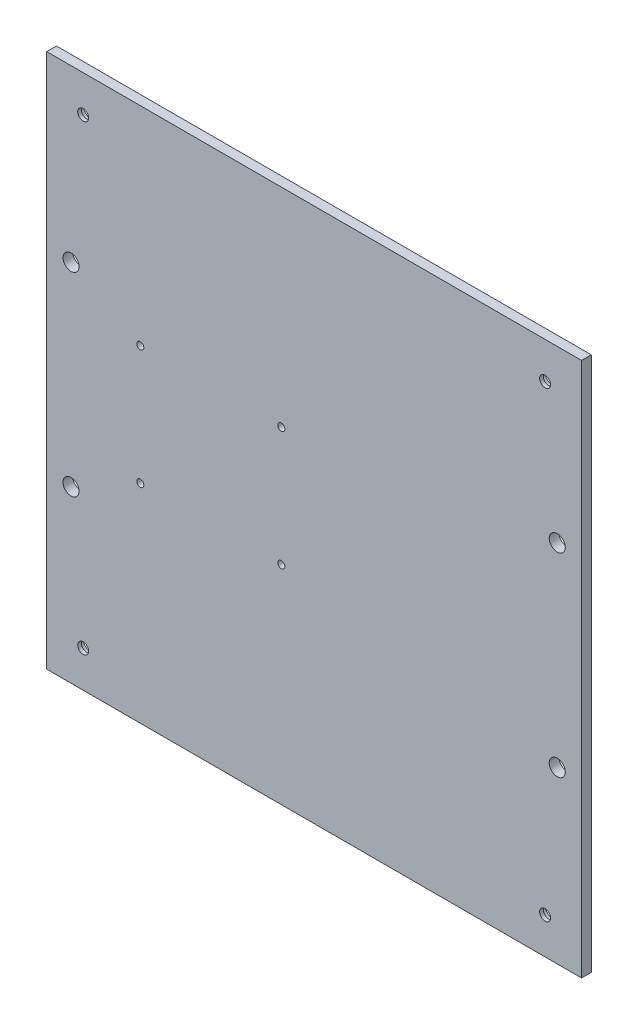
SolidWorks part; units mm, degrees
material "Aleación 6061"
ref_plane "Alzado" through (0, 0, 0) normal (0, 0, 1) x (1, 0, 0)
ref_plane "Planta" through (0, 0, 0) normal (0, 1, 0) x (1, 0, 0)
ref_plane "Vista lateral" through (0, 0, 0) normal (1, 0, 0) x (0, 0, -1)
sketch "Sk_Fondo" plane through (0, 0, 0) normal (0, 0, 1) x (1, 0, 0)
  line L1 (-110, -110) -> (110, -110)
  line L2 (-110, -110) -> (-110, 110)
  line L3 (-110, 110) -> (110, 110)
  line L4 (110, -110) -> (110, 110)
  line L5 (-110, -110) -> (110, 110) construction
  line L6 (-110, 110) -> (110, -110) construction
  point P0 (0, 0)
  dimension "D1" = 220
  dimension "D2" = 220
extrude "Fondo" add sketch "Sk_Fondo" along normal blind 4 from offset 54
sketch "Sk_Pasantes_M4_separadores" plane through (0, 0, 0) normal (0, 0, 1) x (1, 0, 0)
  circle A0 centre (-95, -95) radius 2.25
  circle A1 centre (-95, 95) radius 2.25
  circle A2 centre (95, -95) radius 2.25
  circle A3 centre (95, 95) radius 2.25
  dimension "D1" = 4.5
  dimension "D4" = 4.5
  dimension "D7" = 4.5
  dimension "D10" = 4.5
  dimension "D2" = 95
  dimension "D3" = 95
  dimension "D5" = 95
  dimension "D6" = 95
  dimension "D8" = 95
  dimension "D9" = 95
  dimension "D11" = 95
  dimension "D12" = 95
extrude "Pasantes_M4_separadores" cut sketch "Sk_Pasantes_M4_separadores" along normal blind 4 from offset 54
sketch "Sk_Avellanado_M4" plane through (0, 0, 0) normal (0, 0, 1) x (1, 0, 0)
  circle A0 centre (-95, -95) radius 4.2
  circle A1 centre (-95, 95) radius 4.2
  circle A2 centre (95, -95) radius 4.2
  circle A3 centre (95, 95) radius 4.2
  dimension "D1" = 8.4
  dimension "D4" = 8.4
  dimension "D7" = 8.4
  dimension "D10" = 8.4
  dimension "D2" = 95
  dimension "D3" = 95
  dimension "D5" = 95
  dimension "D6" = 95
  dimension "D8" = 95
  dimension "D9" = 95
  dimension "D11" = 95
  dimension "D12" = 95
extrude "Avellanado_M4" cut sketch "Sk_Avellanado_M4" along normal blind 2.5 from offset 54
sketch "Sk_Pasantes_M2-5_RPi" plane through (0, 0, 0) normal (0, 0, 1) x (1, 0, 0)
  circle A0 centre (-13.5, -24.5) radius 1.45
  circle A1 centre (-13.5, 24.5) radius 1.45
  circle A2 centre (-71.5, -24.5) radius 1.45
  circle A3 centre (-71.5, 24.5) radius 1.45
  dimension "D1" = 2.9
  dimension "D4" = 2.9
  dimension "D7" = 2.9
  dimension "D10" = 2.9
  dimension "D2" = 13.5
  dimension "D3" = 24.5
  dimension "D5" = 13.5
  dimension "D6" = 24.5
  dimension "D8" = 71.5
  dimension "D9" = 24.5
  dimension "D11" = 71.5
  dimension "D12" = 24.5
extrude "Pasantes_M2-5_RPi" cut sketch "Sk_Pasantes_M2-5_RPi" along normal blind 4 from offset 54
sketch "Sk_Avellanado_M2-5" plane through (0, 0, 0) normal (0, 0, 1) x (1, 0, 0)
  circle A0 centre (-13.5, -24.5) radius 2.5
  circle A1 centre (-13.5, 24.5) radius 2.5
  circle A2 centre (-71.5, -24.5) radius 2.5
  circle A3 centre (-71.5, 24.5) radius 2.5
  dimension "D1" = 5
  dimension "D4" = 5
  dimension "D7" = 5
  dimension "D10" = 5
  dimension "D2" = 13.5
  dimension "D3" = 24.5
  dimension "D5" = 13.5
  dimension "D6" = 24.5
  dimension "D8" = 71.5
  dimension "D9" = 24.5
  dimension "D11" = 71.5
  dimension "D12" = 24.5
extrude "Avellanado_M2-5" cut sketch "Sk_Avellanado_M2-5" along normal blind 1.5 from offset 54
sketch "Sk_Agujeros_anclaje" plane through (0, 0, 0) normal (0, 0, 1) x (1, 0, 0)
  circle A0 centre (-100, -40) radius 3.3
  circle A1 centre (-100, 40) radius 3.3
  circle A2 centre (100, -40) radius 3.3
  circle A3 centre (100, 40) radius 3.3
  dimension "D1" = 6.6
  dimension "D4" = 6.6
  dimension "D7" = 6.6
  dimension "D10" = 6.6
  dimension "D2" = 100
  dimension "D3" = 40
  dimension "D5" = 100
  dimension "D6" = 40
  dimension "D8" = 100
  dimension "D9" = 40
  dimension "D11" = 100
  dimension "D12" = 40
extrude "Agujeros_anclaje" cut sketch "Sk_Agujeros_anclaje" along normal blind 4 from offset 54
